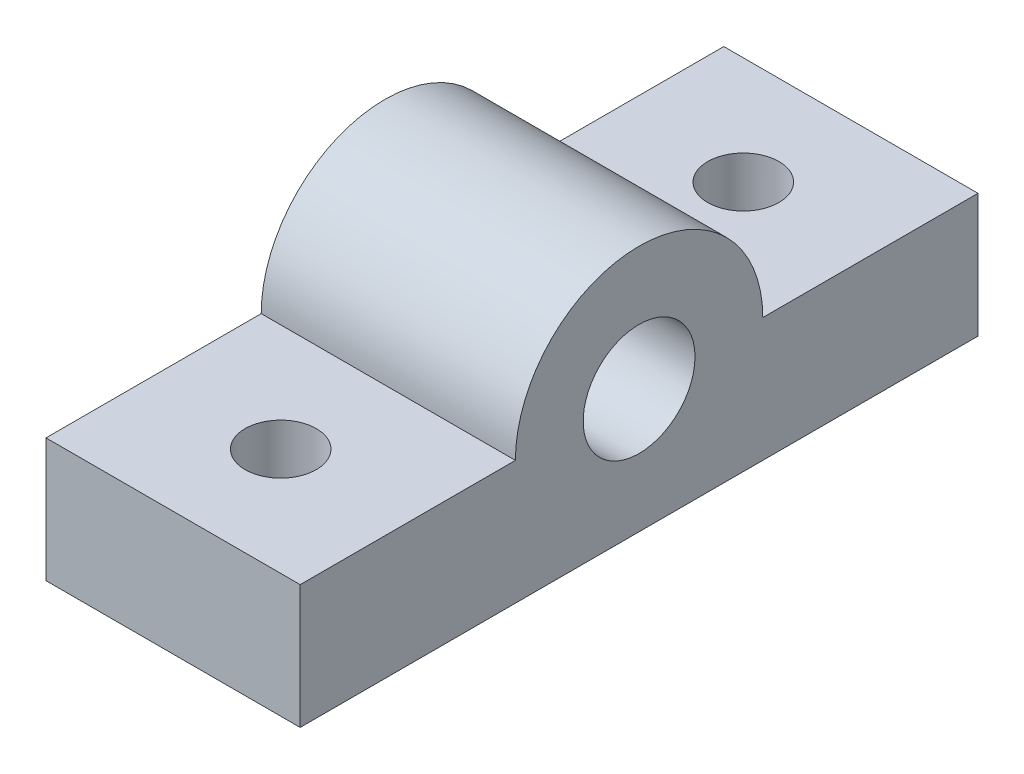
SolidWorks part; units mm, degrees
ref_plane "Alzado" through (0, 0, 0) normal (0, 0, 1) x (1, 0, 0)
ref_plane "Planta" through (0, 0, 0) normal (0, 1, 0) x (1, 0, 0)
ref_plane "Vista lateral" through (0, 0, 0) normal (1, 0, 0) x (0, 0, -1)
sketch "Croquis1" plane through (0, 0, 0) normal (1, 0, 0) x (0, 0, -1)
  line L0 (0, -461.869) -> (0, 22631.5812) construction
  line L1 (-20, 0) -> (20, 0)
  line L2 (20, 0) -> (20, 7.3)
  line L3 (20, 7.3) -> (7.3, 7.3)
  line L4 (-20, 0) -> (-20, 7.3)
  line L5 (-20, 7.3) -> (-7.3, 7.3)
  circle A1 centre (0, 7.3) radius 3.3
  arc A2 (7.3, 7.3) -> (-7.3, 7.3) centre (0, 7.3) ccw
  dimension "D1" = 6.6
  dimension "D2" = 4
  dimension "D3" = 4
  dimension "D4" = 40
extrude "Saliente-Extruir1" add sketch "Croquis1" along normal mid plane 15
sketch "Croquis2" plane through (0, 7.3, 0) normal (0, 1, 0) x (1, 0, 0)
  line L0 (-7.5, -13.65) -> (7.5, -13.65) construction
  line L1 (-7.5, -7.3) -> (-7.5, -20) construction
  line L2 (7.5, -7.3) -> (7.5, -20) construction
  line L6 (-1000, 0) -> (49000, 0) construction
  circle A0 centre (0, -13.65) radius 2.1
  circle A1 centre (0, 13.65) radius 2.1
  dimension "D1" = 4.2
extrude "Cortar-Extruir1" cut sketch "Croquis2" against normal up to next
